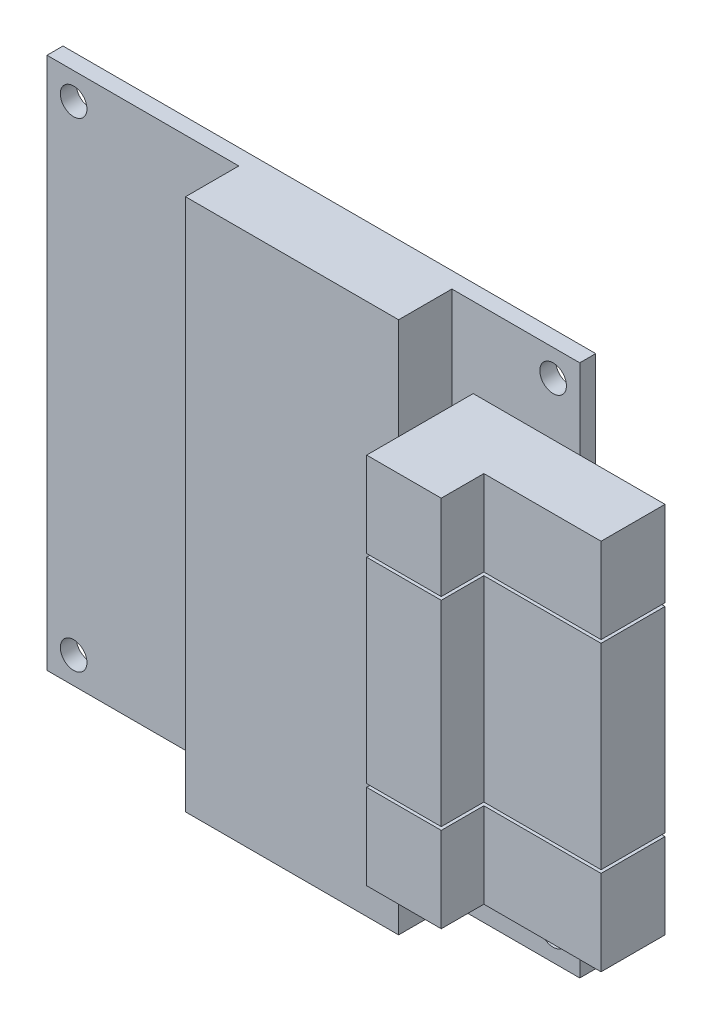
SolidWorks part; units mm, degrees
ref_plane "前视基准面" through (0, 0, 0) normal (0, 0, 1) x (1, 0, 0)
ref_plane "上视基准面" through (0, 0, 0) normal (0, 1, 0) x (1, 0, 0)
ref_plane "右视基准面" through (0, 0, 0) normal (1, 0, 0) x (0, 0, -1)
sketch "草图1" plane through (0, 0, 0) normal (0, 0, 1) x (1, 0, 0)
  line L0 (0, 0) -> (50000, 0) construction
  line L1 (0, 0) -> (0, -50000) construction
  line L3 (25, 25) -> (-25, 25)
  line L4 (25, 25) -> (25, -25)
  line L5 (25, -25) -> (-25, -25)
  line L6 (-25, 25) -> (-25, -25)
extrude "凸台-拉伸1" add sketch "草图1" along normal blind 1.5
sketch "草图2" plane through (0, 0, 1.5) normal (0, 0, 1) x (1, 0, 0)
  line L0 (0, 0) -> (0, -50000) construction
  line L1 (0, 0) -> (50000, 0) construction
  line L2 (25, 25) -> (-25, 25) construction
  line L3 (13, 25) -> (-7, 25)
  line L4 (13, 25) -> (13, -25)
  line L5 (13, -25) -> (-7, -25)
  line L6 (-7, 25) -> (-7, -25)
  line L7 (-25, -25) -> (25, -25) construction
  line L8 (-25, 25) -> (-25, -25) construction
  line L9 (25, -25) -> (25, 25) construction
  dimension "D1" = 18
  dimension "D2" = 12
extrude "凸台-拉伸2" add sketch "草图2" along normal blind 5 contours L4 L3 L6 L5
sketch "草图3" plane through (0, 0, 1.5) normal (0, 0, 1) x (1, 0, 0)
  line L0 (0, 0) -> (50000, 0) construction
  line L1 (15, 17.5) -> (33, 17.5)
  line L2 (15, 17.5) -> (15, 9.5)
  line L3 (15, 9.5) -> (33, 9.5)
  line L4 (33, 17.5) -> (33, 9.5)
  line L5 (15, 9.2) -> (33, 9.2)
  line L6 (15, 9.2) -> (15, -9.2)
  line L7 (15, -9.2) -> (33, -9.2)
  line L8 (33, 9.2) -> (33, -9.2)
  line L9 (15, -9.5) -> (33, -9.5)
  line L10 (33, -17.5) -> (33, -9.5)
  line L11 (15, -17.5) -> (33, -17.5)
  line L12 (15, -17.5) -> (15, -9.5)
  line L13 (25, -25) -> (25, 25) construction
  line L14 (25, 25) -> (13, 25) construction
  dimension "D1" = 10
  dimension "D2" = 7.5
  dimension "D3" = 18
  dimension "D4" = 18.4
  dimension "D5" = 8
extrude "凸台-拉伸3" add sketch "草图3" along normal blind 10
sketch "草图4" plane through (0, -17.5, 0) normal (0, -1, 0) x (1, 0, 0)
  line L0 (15, 11.5) -> (15, 1.5) construction
  line L1 (33, 11.5) -> (22, 11.5)
  line L2 (33, 11.5) -> (33, 7.5)
  line L3 (33, 7.5) -> (22, 7.5)
  line L4 (22, 11.5) -> (22, 7.5)
  dimension "D1" = 7
  dimension "D2" = 4
extrude "切除-拉伸1" cut sketch "草图4" against normal through all
sketch "草图5" plane through (0, 0, 1.5) normal (0, 0, 1) x (1, 0, 0)
  line L0 (-25, 25) -> (-25, -25) construction
  line L1 (-7, 25) -> (-25, 25) construction
  line L2 (25, 17.5) -> (25, 25) construction
  line L3 (25, 25) -> (13, 25) construction
  line L4 (25, -25) -> (25, -17.5) construction
  line L5 (13, -25) -> (25, -25) construction
  line L6 (-25, -25) -> (-7, -25) construction
  circle A0 centre (-22.5, 22.5) radius 1.25
  circle A1 centre (22.5, 22.5) radius 1.25
  circle A2 centre (22.5, -22.5) radius 1.25
  circle A3 centre (-22.5, -22.5) radius 1.25
  dimension "D3" = 2.5
  dimension "D4" = 2.5
  dimension "D5" = 2.5
  dimension "D6" = 2.5
  dimension "D7" = 2.5
  dimension "D8" = 2.5
  dimension "D9" = 2.5
  dimension "D10" = 2.5
  dimension "D11" = 2.5
  dimension "D12" = 2.5
  dimension "D1" = 2.5
  dimension "D2" = 2.5
extrude "切除-拉伸2" cut sketch "草图5" against normal through all
